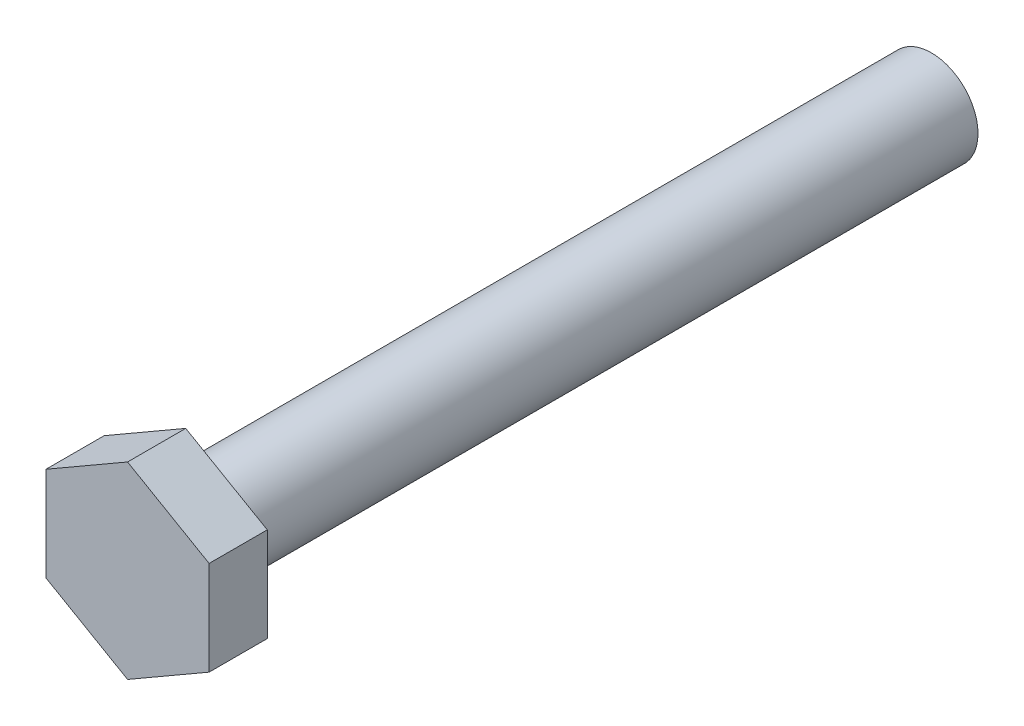
SolidWorks part; units mm, degrees
ref_plane "Front" through (0, 0, 0) normal (0, 0, 1) x (1, 0, 0)
ref_plane "Top" through (0, 0, 0) normal (0, 1, 0) x (1, 0, 0)
ref_plane "Right" through (0, 0, 0) normal (1, 0, 0) x (0, 0, -1)
sketch "Sketch1" plane through (0, 0, 0) normal (0, 0, 1) x (1, 0, 0)
  circle A0 centre (0, 0) radius 3.175
  dimension "D1" = 6.35
extrude "Boss-Extrude1" add sketch "Sketch1" along normal blind 50.8
sketch "Sketch2" plane through (0, 0, 50.8) normal (0, 0, 1) x (1, 0, 0)
  line L1 (5.5562, 3.2079) -> (0, 6.4158)
  line L2 (0, 6.4158) -> (-5.5562, 3.2079)
  line L3 (-5.5562, 3.2079) -> (-5.5562, -3.2079)
  line L4 (-5.5562, -3.2079) -> (0, -6.4158)
  line L5 (0, -6.4158) -> (5.5562, -3.2079)
  line L6 (5.5562, -3.2079) -> (5.5562, 3.2079)
  dimension "D1" = 11.1125
extrude "Boss-Extrude2" add sketch "Sketch2" along normal blind 3.9624
